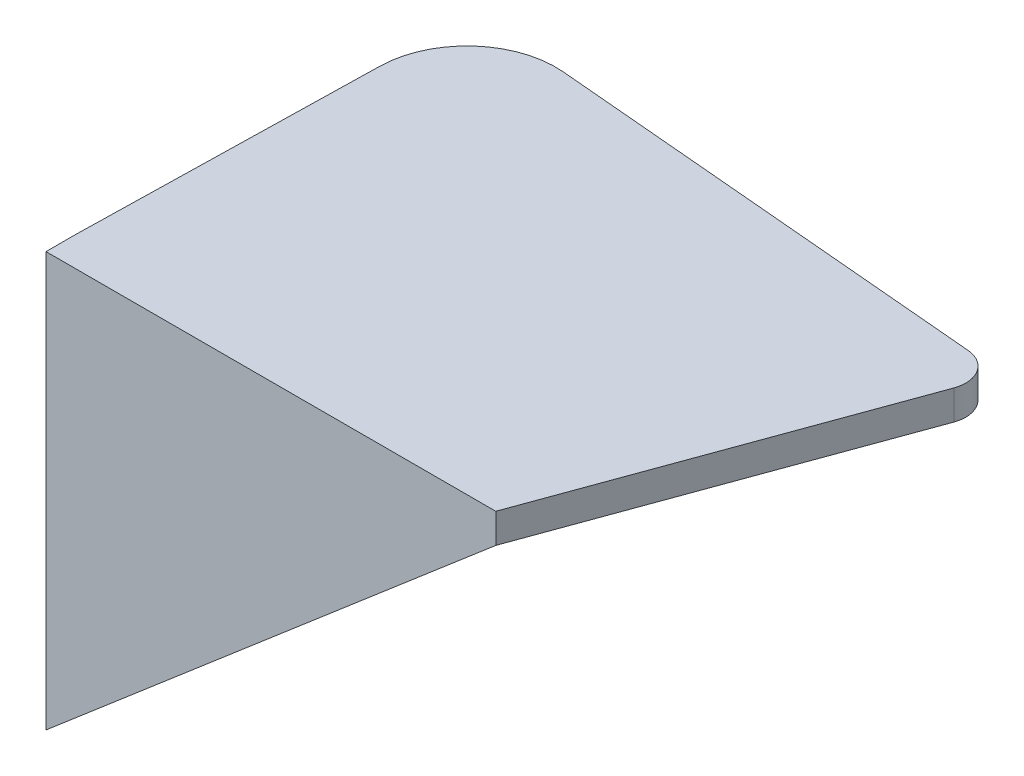
SolidWorks part; units mm, degrees
material "5052-H38, Rod (SS)"
ref_plane "Front Plane" through (0, 0, 0) normal (0, 0, 1) x (1, 0, 0)
ref_plane "Top Plane" through (0, 0, 0) normal (0, 1, 0) x (1, 0, 0)
ref_plane "Right Plane" through (0, 0, 0) normal (1, 0, 0) x (0, 0, -1)
sketch "Sketch1" plane through (0, 0, 0) normal (0, 0, 1) x (1, 0, 0)
  line L0 (0, 0) -> (151.9868, 0)
  line L1 (151.9868, 0) -> (0, -130)
  line L2 (0, -130) -> (0, 0)
  dimension "D1" = 200
  dimension "D2" = 130
sketch "Sketch2" plane through (0, 0, 0) normal (0, 1, 0) x (1, 0, 0)
  line L0 (0, 0) -> (151.9868, 0)
  line L2 (151.9868, 0) -> (193.3137, -113.5445)
  line L3 (35.3591, -140) -> (184.7883, -126.9266)
  line L4 (0, 0) -> (0, -10)
  line L5 (0, -10) -> (2.7556, -110.9329)
  arc A0 (184.7883, -126.9266) -> (193.3137, -113.5445) centre (183.9167, -116.9647) ccw
  arc A2 (35.3591, -140) -> (2.7556, -110.9329) centre (32.7444, -110.1142) cw
  dimension "D3" = 10
  dimension "D4" = 30
  dimension "D1" = 110
  dimension "D2" = 75
  dimension "D5" = 10
  dimension "D6" = 150
  dimension "D7" = 140
extrude "Boss-Extrude1" [suppressed] add sketch "Sketch1" along normal blind 10
extrude "Boss-Extrude2" [suppressed] add sketch "Sketch2" along normal blind 10
sketch "Sketch3" plane through (0, 0, 0) normal (0, 0, 1) x (1, 0, 0)
  line L0 (0, 0) -> (151.9868, 0)
  line L1 (151.9868, 0) -> (0, -130)
  line L2 (0, -130) -> (0, 0)
  dimension "D1" = 200
  dimension "D2" = 130
sketch "Sketch5" plane through (0, 0, 0) normal (0, 1, 0) x (1, 0, 0)
  line L0 (0, 0) -> (151.9868, 0)
  line L2 (151.9868, 0) -> (193.2955, 113.4946)
  line L3 (34.7701, 140) -> (184.7701, 126.8767)
  line L4 (0, 0) -> (0, 10)
  line L5 (0, 10) -> (2.1623, 110.7578)
  arc A0 (34.7701, 140) -> (2.1623, 110.7578) centre (32.1554, 110.1142) ccw
  arc A1 (193.2955, 113.4946) -> (184.7701, 126.8767) centre (183.8986, 116.9148) ccw
  dimension "D4" = 30
  dimension "D5" = 10
  dimension "D1" = 110
  dimension "D2" = 140
  dimension "D3" = 10
  dimension "D6" = 75
  dimension "D7" = 150
extrude "Boss-Extrude3" add sketch "Sketch3" against normal blind 10 separate body
extrude "Boss-Extrude4" add sketch "Sketch5" along normal blind 10
